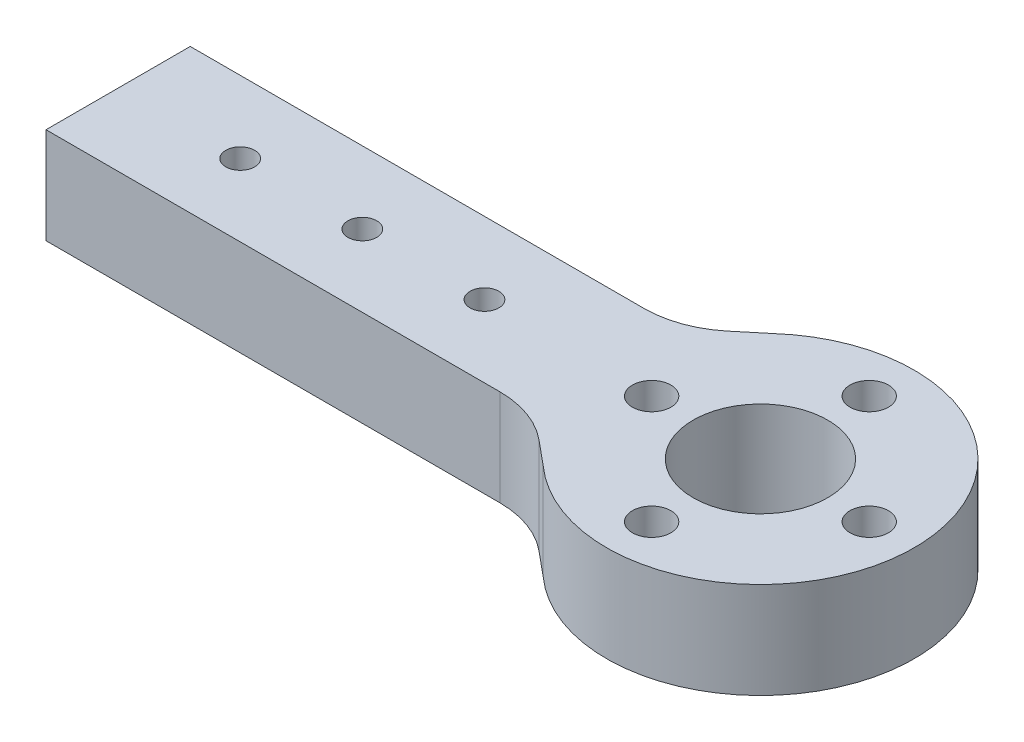
SolidWorks part; units mm, degrees
ref_plane "Front" through (0, 0, 0) normal (0, 0, 1) x (1, 0, 0)
ref_plane "Top" through (0, 0, 0) normal (0, 1, 0) x (1, 0, 0)
ref_plane "Right" through (0, 0, 0) normal (1, 0, 0) x (0, 0, -1)
sketch "Sketch1" plane through (0, 0, 0) normal (0, 1, 0) x (1, 0, 0)
  line L0 (23.1155, 15) -> (47.1915, 15)
  line L1 (0, 0) -> (50.8, 0)
  line L2 (0, 0) -> (0, 15)
  line L3 (0, 15) -> (23.1155, 15)
  line L4 (50.8, 0) -> (50.8, 15)
  line L5 (50.8, 7.5) -> (66.8, 7.5)
  line L6 (50.8, 0) -> (28.0325, 0)
  line L7 (53.577, 17.3042) -> (56.1261, 19.4192)
  line L8 (53.577, -2.3042) -> (56.1261, -4.4192)
  line L9 (0, 7.5) -> (50.8, 7.5)
  line L10 (25.4, 7.5) -> (50.8, 7.5)
  line L11 (25.4, 7.5) -> (0, 7.5)
  circle A2 centre (66.8, 7.5) radius 16
  circle A3 centre (66.8, 7.5) radius 11.3137
  circle A4 centre (25.4, 7.5) radius 1.5
  circle A5 centre (38.1, 7.5) radius 1.5
  circle A6 centre (12.7, 7.5) radius 1.5
  circle A7 centre (78.1137, 7.5) radius 2
  circle A8 centre (66.8, 18.8137) radius 2
  circle A9 centre (55.4863, 7.5) radius 2
  circle A10 centre (66.8, -3.8137) radius 2
  arc A11 (53.577, 17.3042) -> (47.1915, 15) centre (47.1915, 25) cw
  arc A12 (53.577, -2.3042) -> (47.1915, 0) centre (47.1915, -10) ccw
  circle A13 centre (66.8, 7.5) radius 7
  dimension "D4" = 10
  dimension "D1" = 50.8
  dimension "D2" = 15
  dimension "D3" = 16
extrude "Boss-Extrude1" add sketch "Sketch1" along normal blind 10
